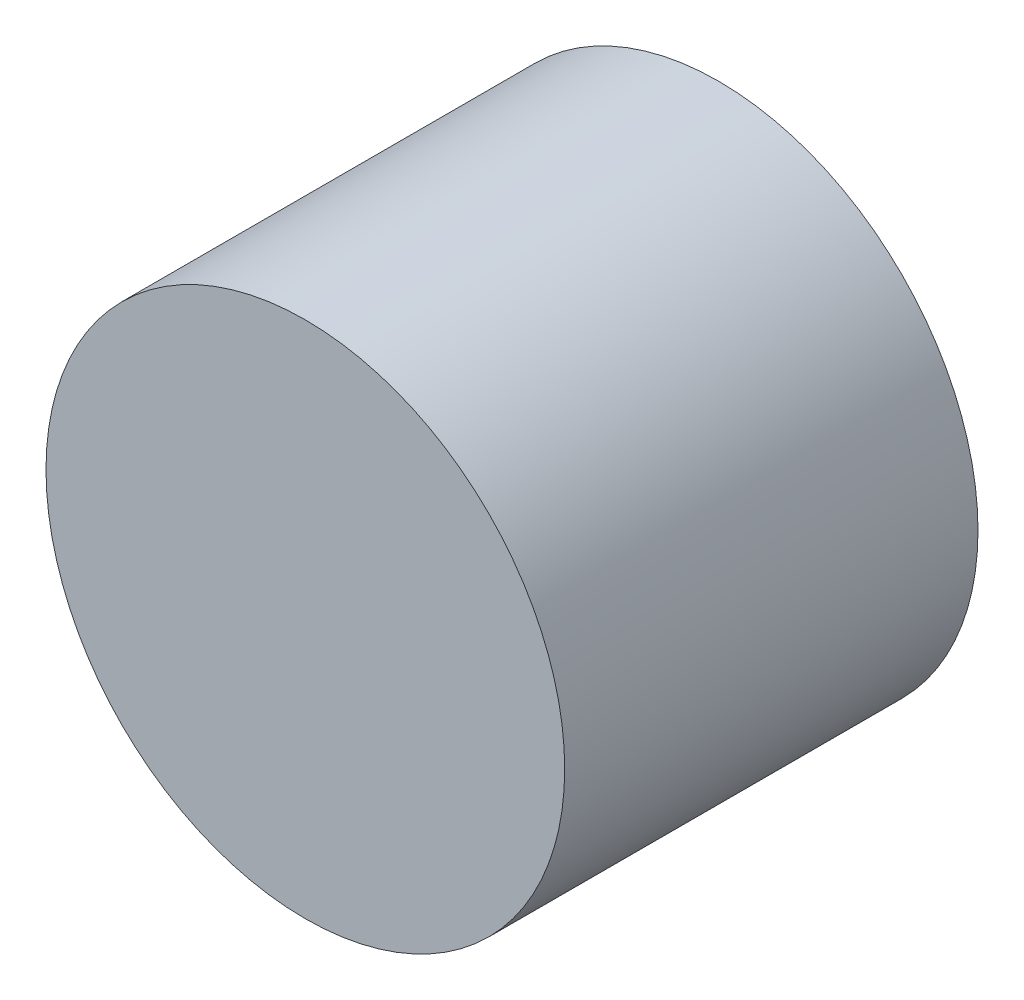
SolidWorks part; units mm, degrees
material "authored material"
ref_plane "Front Plane" through (0, 0, 0) normal (0, 0, 1) x (1, 0, 0)
ref_plane "Top Plane" through (0, 0, 0) normal (0, 1, 0) x (1, 0, 0)
ref_plane "Right Plane" through (0, 0, 0) normal (1, 0, 0) x (0, 0, -1)
sketch "Sketch1" plane through (0, 0, 0) normal (0, 0, 1) x (1, 0, 0)
  circle A0 centre (-4.913, 6.281) radius 7.639
  dimension "D1" = 7.639
extrude "Boss-Extrude1" add sketch "Sketch1" along normal blind 12.173
